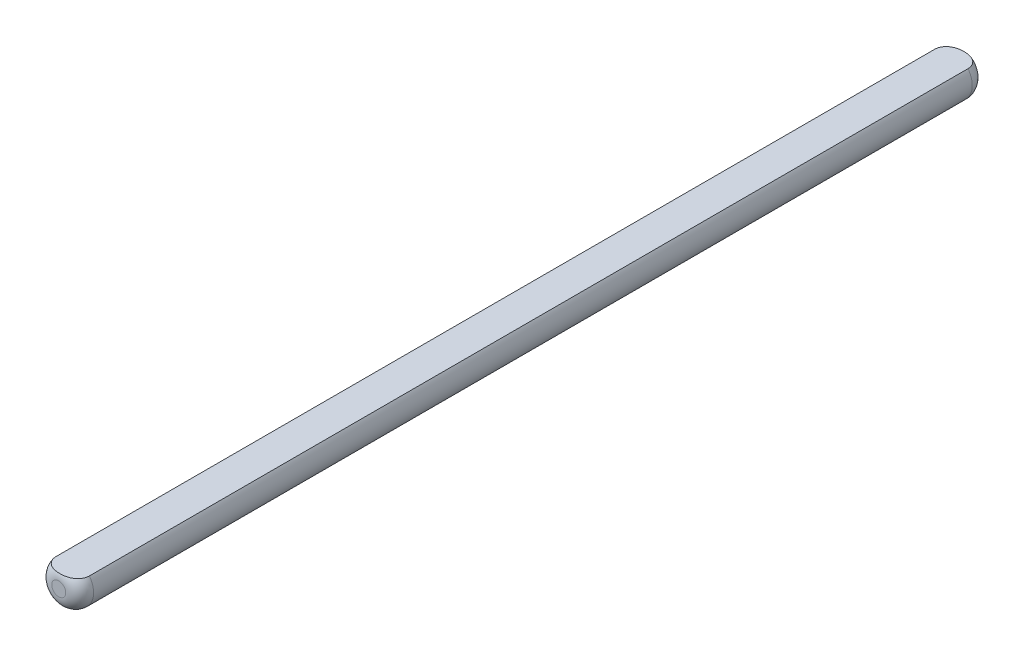
SolidWorks part; units mm, degrees
ref_plane "Plan de face" through (0, 0, 0) normal (0, 0, 1) x (1, 0, 0)
ref_plane "Plan de dessus" through (0, 0, 0) normal (0, 1, 0) x (1, 0, 0)
ref_plane "Plan de droite" through (0, 0, 0) normal (1, 0, 0) x (0, 0, -1)
sketch "Esquisse1" plane through (0, 0, 0) normal (0, 0, 1) x (1, 0, 0)
  circle A0 centre (0, 0) radius 3
  dimension "D1" = 6
extrude "Boss.-Extru.1" add sketch "Esquisse1" along normal blind 130
fillet "Congé1" radius 2 2 edges at (3, 0, 0) (3, 0, 130)
sketch "Esquisse2" plane through (0, 0, 130) normal (0, 0, 1) x (1, 0, 0)
  line L1 (-3, 3) -> (3, 3)
  line L2 (-3, 3) -> (-3, 1.8)
  line L3 (-3, 1.8) -> (3, 1.8)
  line L4 (3, 3) -> (3, 1.8)
  circle A0 centre (0, 0) radius 3 construction
  point P6 (0, 3)
  dimension "D1" = 6
  dimension "D2" = 1.2
extrude "Enlèv. mat.-Extru.1" cut sketch "Esquisse2" against normal through all
